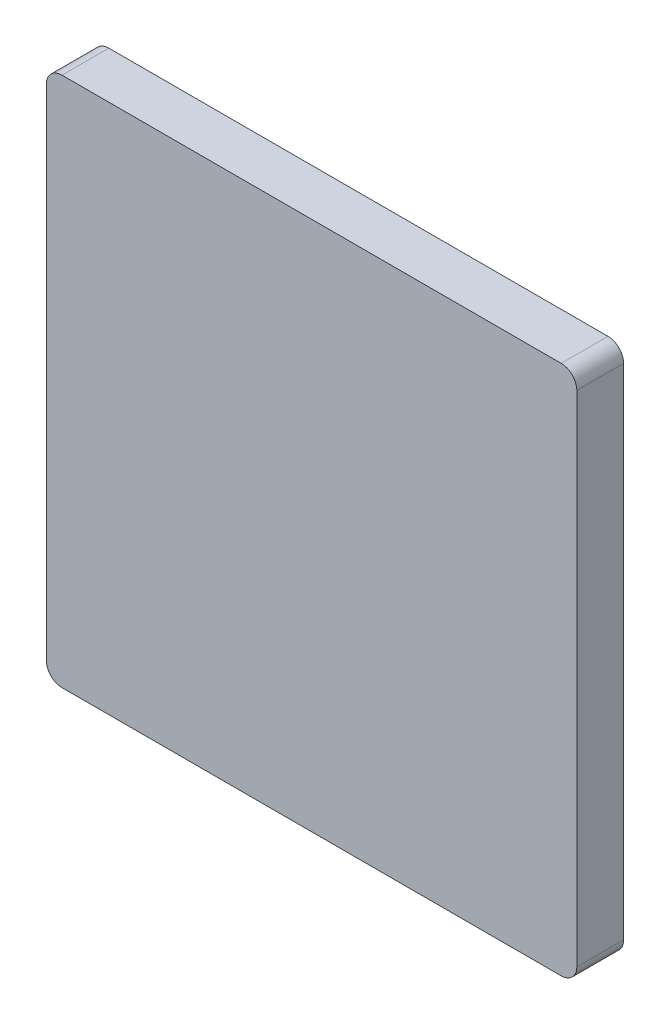
SolidWorks part; units mm, degrees
material "硅"
ref_plane "前视基准面" through (0, 0, 0) normal (0, 0, 1) x (1, 0, 0)
ref_plane "上视基准面" through (0, 0, 0) normal (0, 1, 0) x (1, 0, 0)
ref_plane "右视基准面" through (0, 0, 0) normal (1, 0, 0) x (0, 0, -1)
sketch "草图1" plane through (0, 0, 0) normal (0, 0, 1) x (1, 0, 0)
  line L1 (0, 0) -> (6.8, 0)
  line L2 (0, 0) -> (0, 6.8)
  line L3 (0, 6.8) -> (6.8, 6.8)
  line L4 (6.8, 0) -> (6.8, 6.8)
  dimension "D1" = 6.8
  dimension "D2" = 6.8
extrude "凸台-拉伸1" add sketch "草图1" along normal blind 0.6
fillet "圆角1" radius 0.2 4 edges at (0, 0, 0.3) (6.8, 0, 0.3) (6.8, 6.8, 0.3) (0, 6.8, 0.3)
